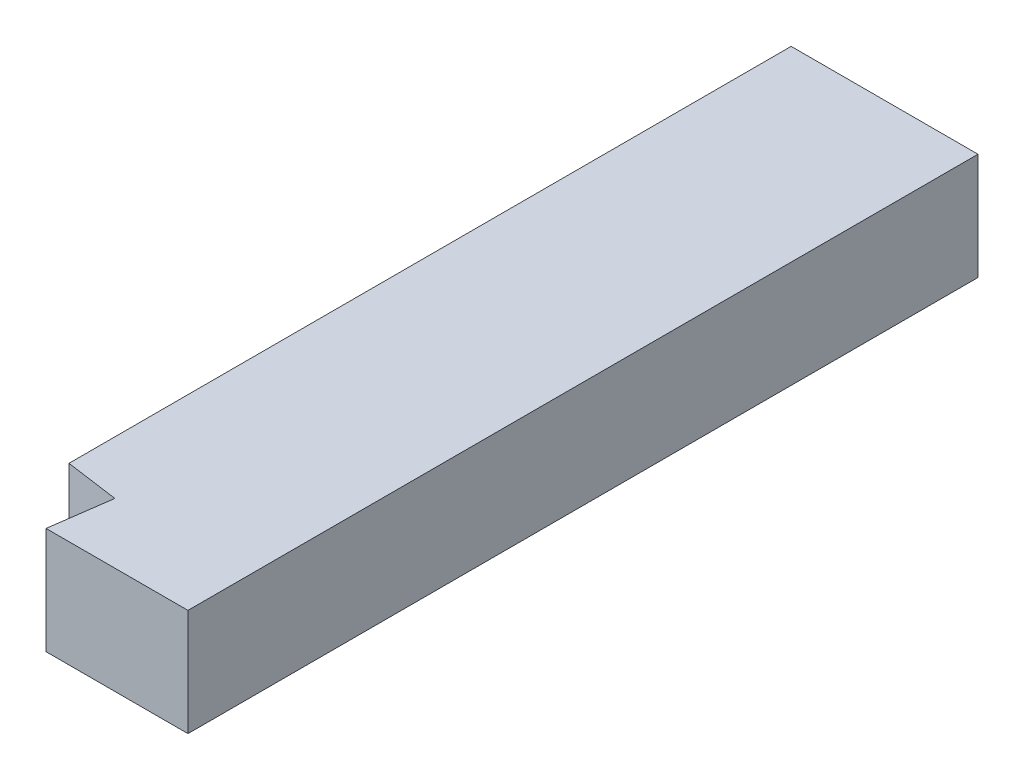
SolidWorks part; units mm, degrees
material "Pine"
ref_plane "X-Y Datum" through (0, 0, 0) normal (0, 0, 1) x (1, 0, 0)
ref_plane "X-Z Datum" through (0, 0, 0) normal (0, 1, 0) x (1, 0, 0)
ref_plane "Y-Z Datum" through (0, 0, 0) normal (1, 0, 0) x (0, 0, -1)
sketch "Sketch1" plane through (0, 0, 0) normal (0, 0, 1) x (1, 0, 0)
  line L1 (-50.8, 25.4) -> (50.8, 25.4)
  line L2 (-50.8, 25.4) -> (-50.8, -25.4)
  line L3 (-50.8, -25.4) -> (50.8, -25.4)
  line L4 (50.8, 25.4) -> (50.8, -25.4)
  line L5 (-50.8, 25.4) -> (50.8, -25.4) construction
  line L6 (-50.8, -25.4) -> (50.8, 25.4) construction
  point P0 (0, 0)
  dimension "D1" = 101.6
  dimension "D2" = 50.8
extrude "Boss-Extrude1" add sketch "Sketch1" along normal blind 375.9072
sketch "Sketch2" plane through (0, 25.4, 0) normal (0, 1, 0) x (1, 0, 0)
  line L1 (-50.8, -343.6101) -> (-25.4, -347.1798)
  line L3 (-50.8, -375.9072) -> (-50.8, 0) construction
  line L7 (-25.4, -347.1798) -> (-29.4374, -375.9072)
  line L8 (-50.8, -375.9072) -> (-50.8, 0) construction
  line L9 (-50.8, -375.9072) -> (50.8, -375.9072) construction
  line L10 (-50.8, -343.6101) -> (-50.8, -375.9072)
  line L11 (-50.8, -375.9072) -> (-29.4374, -375.9072)
  dimension "D2" = 29.0097
  dimension "D1" = 98
  dimension "D6" = 25.4
extrude "Cut-Extrude1" cut sketch "Sketch2" against normal through all both and the other way through all
sketch "Sketch3" plane through (0, 25.4, 0) normal (0, 1, 0) x (1, 0, 0)
  line L0 (50.8, 0) -> (-50.8, 0) construction
  line L1 (50.8, -375.9072) -> (38.1, -375.9072)
  line L2 (50.8, -375.9072) -> (50.8, 0)
  line L3 (50.8, 0) -> (38.1, 0)
  line L4 (38.1, -375.9072) -> (38.1, 0)
  line L5 (-50.8, -343.6101) -> (-50.8, 0) construction
  dimension "D1" = 88.9
extrude "Cut-Extrude2" cut sketch "Sketch3" against normal through all both
